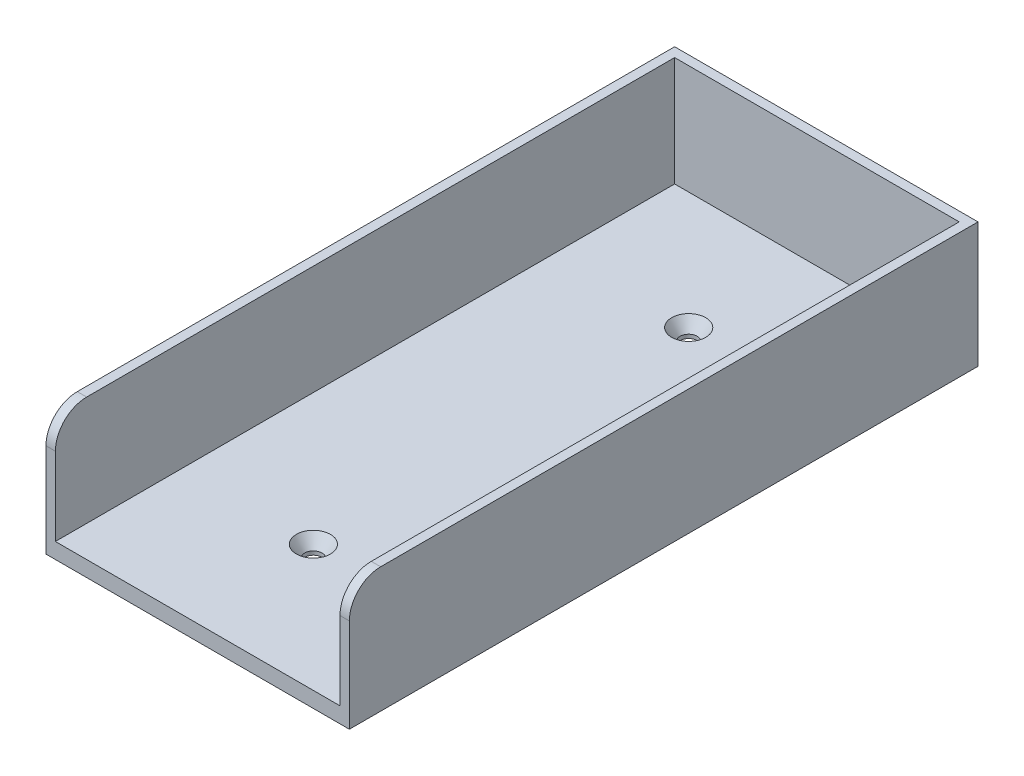
SolidWorks part; units mm, degrees
ref_plane "Front Plane" through (0, 0, 0) normal (0, 0, 1) x (1, 0, 0)
ref_plane "Top Plane" through (0, 0, 0) normal (0, 1, 0) x (1, 0, 0)
ref_plane "Right Plane" through (0, 0, 0) normal (1, 0, 0) x (0, 0, -1)
sketch "Sketch1" plane through (0, 0, 0) normal (0, 1, 0) x (1, 0, 0)
  line L0 (-45.5, -97.5) -> (-45.5, -100.5)
  line L2 (-45.5, -97.5) -> (-45.5, 97.5)
  line L3 (-45.5, 97.5) -> (45.5, 97.5)
  line L4 (45.5, -97.5) -> (45.5, 97.5)
  line L5 (-45.5, -97.5) -> (45.5, 97.5) construction
  line L6 (-45.5, 97.5) -> (45.5, -97.5) construction
  line L7 (-48.5, -100.5) -> (-45.5, -100.5)
  line L8 (-48.5, -100.5) -> (-48.5, 100.5)
  line L9 (-48.5, 100.5) -> (48.5, 100.5)
  line L10 (48.5, -100.5) -> (48.5, 100.5)
  line L11 (-48.5, -100.5) -> (48.5, 100.5) construction
  line L12 (-48.5, 100.5) -> (48.5, -100.5) construction
  line L13 (45.5, -97.5) -> (45.5, -100.5)
  line L14 (45.5, -100.5) -> (48.5, -100.5)
  point P0 (0, 0)
  point P6 (0, 0)
  dimension "D1" = 91
  dimension "D2" = 195
  dimension "D3" = 3
  dimension "D4" = 3
extrude "Boss-Extrude1" add sketch "Sketch1" along normal blind 35
sketch "Sketch3" plane through (0, 0, 0) normal (0, -1, 0) x (1, 0, 0)
  line L1 (-48.5, 100.5) -> (48.5, 100.5)
  line L2 (-48.5, 100.5) -> (-48.5, -100.5)
  line L3 (-48.5, -100.5) -> (48.5, -100.5)
  line L4 (48.5, 100.5) -> (48.5, -100.5)
extrude "Boss-Extrude2" add sketch "Sketch3" along normal blind 5
fillet "Fillet1" radius 10 2 edges at (47, 35, 100.5) (-47, 35, 100.5)
sketch "Sketch4" plane through (0, 0, 0) normal (0, 1, 0) x (1, 0, 0)
  line L0 (-3.5, 60) -> (-3.5, -60) construction
  line L1 (-48.5, 100.5) -> (-48.5, -90.5) construction
  circle A0 centre (-3.5, 60) radius 2.75
  circle A1 centre (-3.5, -60) radius 2.75
  dimension "D2" = 5.5
  dimension "D5" = 5.5
  dimension "D1" = 45
  dimension "D3" = 120
  dimension "D4" = 60
extrude "Cut-Extrude1" cut sketch "Sketch4" against normal blind 10
chamfer "Chamfer3" distance 2.7 distance2 3.8 1 edges at (-3.5, 0, 62.75)
chamfer "Chamfer4" distance 2.7 distance2 3.8 1 edges at (-3.5, 0, -57.25)
